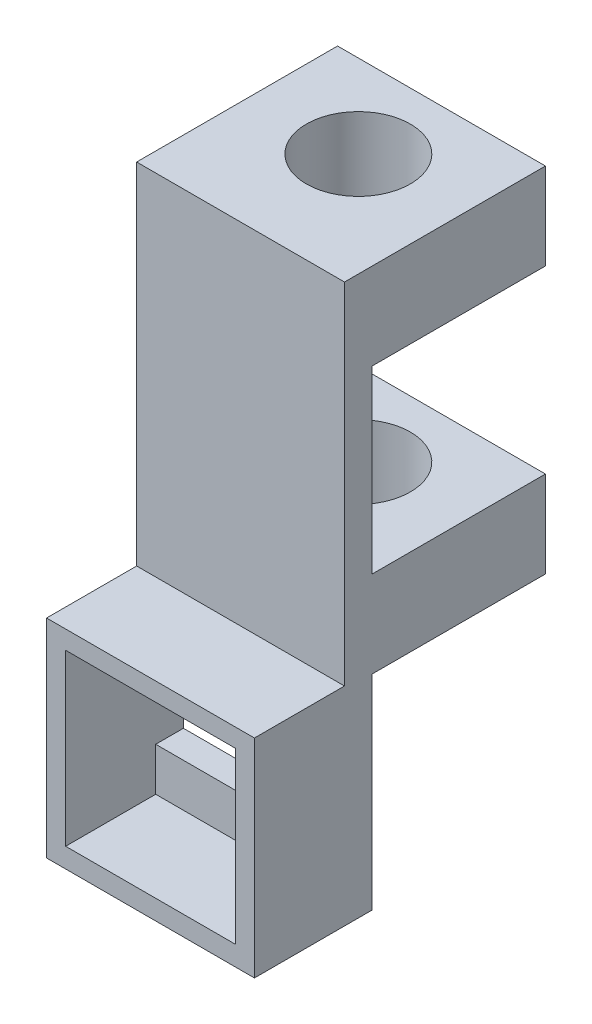
SolidWorks part; units mm, degrees
ref_plane "Front Plane" through (0, 0, 0) normal (0, 0, 1) x (1, 0, 0)
ref_plane "Top Plane" through (0, 0, 0) normal (0, 1, 0) x (1, 0, 0)
ref_plane "Right Plane" through (0, 0, 0) normal (1, 0, 0) x (0, 0, -1)
sketch "Sketch1" plane through (0, 0, 0) normal (0, 0, 1) x (1, 0, 0)
  line L1 (-3.81, -10.2235) -> (3.81, -10.2235)
  line L2 (-3.81, -10.2235) -> (-3.81, 10.2235)
  line L3 (-3.81, 10.2235) -> (3.81, 10.2235)
  line L4 (3.81, -10.2235) -> (3.81, 10.2235)
  line L5 (-3.81, -10.2235) -> (3.81, 10.2235) construction
  line L6 (-3.81, 10.2235) -> (3.81, -10.2235) construction
  point P0 (0, 0)
  dimension "D1" = 20.447
  dimension "D2" = 7.62
extrude "Boss-Extrude1" add sketch "Sketch1" along normal blind 1.016
sketch "Sketch2" plane through (0, 0, 0) normal (0, 0, -1) x (-1, 0, 0)
  line L1 (-3.81, 10.2235) -> (3.81, 10.2235)
  line L2 (-3.81, 10.2235) -> (-3.81, 7.0485)
  line L3 (-3.81, 7.0485) -> (3.81, 7.0485)
  line L4 (3.81, 10.2235) -> (3.81, 7.0485)
  line L5 (3.81, 10.2235) -> (3.81, -10.2235) construction
  line L7 (-3.81, 0.4445) -> (3.81, 0.4445)
  line L8 (-3.81, 0.4445) -> (-3.81, -2.7305)
  line L9 (-3.81, -2.7305) -> (3.81, -2.7305)
  line L10 (3.81, 0.4445) -> (3.81, -2.7305)
  line L11 (-3.81, -10.2235) -> (-3.81, 10.2235) construction
  dimension "D1" = 3.175
  dimension "D2" = 7.62
  dimension "D3" = 3.175
  dimension "D4" = 7.62
  dimension "D5" = 6.604
extrude "Boss-Extrude2" add sketch "Sketch2" along normal blind 6.35
sketch "Sketch3" plane through (0, 10.2235, 0) normal (0, 1, 0) x (1, 0, 0)
  line L0 (-3.81, 6.35) -> (3.81, 6.35) construction
  circle A0 centre (0, 3.302) radius 1.905
  dimension "D1" = 3.81
  dimension "D2" = 3.048
extrude "Cut-Extrude1" cut sketch "Sketch3" against normal through all
sketch "Sketch5" plane through (0, 0, 1.016) normal (0, 0, 1) x (1, 0, 0)
  line L1 (-3.81, -2.6035) -> (3.81, -2.6035)
  line L2 (-3.81, -2.6035) -> (-3.81, -10.2235)
  line L3 (-3.81, -10.2235) -> (3.81, -10.2235)
  line L4 (3.81, -2.6035) -> (3.81, -10.2235)
  line L5 (-3.1115, -9.5018) -> (3.1115, -9.5018)
  line L6 (-3.1115, -9.5018) -> (-3.1115, -3.2788)
  line L7 (-3.1115, -3.2788) -> (3.1115, -3.2788)
  line L8 (3.1115, -9.5018) -> (3.1115, -3.2788)
  line L9 (-3.1115, -9.5018) -> (3.1115, -3.2788) construction
  line L10 (-3.1115, -3.2788) -> (3.1115, -9.5018) construction
  point P0 (0, -6.3903)
  point P5 (0, -6.3903)
  point P11 (0, -3.2788)
  point P12 (0, -2.6035)
  dimension "D1" = 7.62
  dimension "D2" = 7.62
  dimension "D3" = 6.223
  dimension "D4" = 6.223
  dimension "D5" = 0
extrude "Boss-Extrude3" add sketch "Sketch5" along normal blind 3.302
sketch "Sketch7" plane through (0, 0, 1.016) normal (0, 0, 1) x (1, 0, 0)
  line L7 (3.1115, -9.5018) -> (3.1115, -3.2788) construction
  line L8 (-3.1115, -7.9143) -> (-1.524, -7.9143)
  line L9 (-3.1115, -7.9143) -> (-3.1115, -4.8663)
  line L10 (-3.1115, -4.8663) -> (-1.524, -4.8663)
  line L11 (3.1115, -7.9143) -> (3.1115, -4.8663)
  line L12 (1.524, -7.9143) -> (3.1115, -7.9143)
  line L13 (1.524, -4.8663) -> (3.1115, -4.8663)
  line L14 (-1.524, -4.8663) -> (1.524, -4.8663)
  line L15 (-1.524, -7.9143) -> (1.524, -7.9143)
  point P0 (0, -6.3903)
  point P7 (0, -6.3903)
  dimension "D3" = 3.048
  dimension "D4" = 6.223
extrude "Cut-Extrude3" cut sketch "Sketch7" against normal through all
